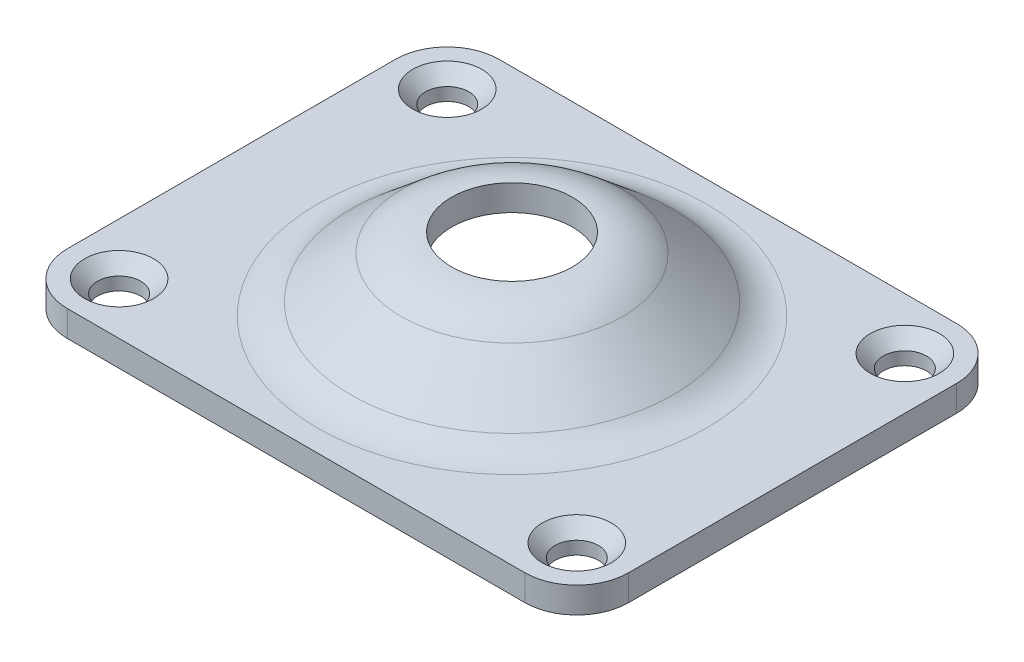
SolidWorks part; units mm, degrees
material "1023 Carbon Steel Sheet (SS)"
ref_plane "Front Plane" through (0, 0, 0) normal (0, 0, 1) x (1, 0, 0)
ref_plane "Top Plane" through (0, 0, 0) normal (0, 1, 0) x (1, 0, 0)
ref_plane "Right Plane" through (0, 0, 0) normal (1, 0, 0) x (0, 0, -1)
sketch "Sketch1" plane through (0, 0, 0) normal (0, 1, 0) x (1, 0, 0)
  line L1 (-26.5, 25) -> (26.5, 25)
  line L2 (-32.5, 19) -> (-32.5, -19)
  line L3 (-26.5, -25) -> (26.5, -25)
  line L4 (32.5, 19) -> (32.5, -19)
  line L5 (-32.5, 25) -> (32.5, -25) construction
  line L6 (-32.5, -25) -> (32.5, 25) construction
  circle A0 centre (-26.5, 19) radius 2.5
  circle A1 centre (26.5, 19) radius 2.5
  circle A2 centre (-26.5, -19) radius 2.5
  circle A3 centre (26.5, -19) radius 2.5
  arc A4 (-32.5, -19) -> (-26.5, -25) centre (-26.5, -19) ccw
  arc A5 (26.5, -25) -> (32.5, -19) centre (26.5, -19) ccw
  arc A6 (26.5, 25) -> (32.5, 19) centre (26.5, 19) cw
  arc A7 (-26.5, 25) -> (-32.5, 19) centre (-26.5, 19) ccw
  circle A8 centre (0, 0) radius 22.5
  point P0 (0, 0)
  dimension "D1" = 6
  dimension "D2" = 5
  dimension "D5" = 45
  dimension "D3" = 65
  dimension "D4" = 50
extrude "Boss-Extrude1" add sketch "Sketch1" along normal blind 3
chamfer "Chamfer1" distance 1.5 angle 45 4 edges at (-26.5, 3, 21.5) (26.5, 3, 21.5) (26.5, 3, -16.5) (-26.5, 3, -16.5)
sketch "Sketch4" plane through (0, 0, 0) normal (0, 0, 1) x (1, 0, 0)
  line L0 (-22.5, 0) -> (-22.5, 3)
  line L1 (26.5, 0) -> (-26.5, 0) construction
  line L2 (-22.5, 0) -> (22.5, 0) construction
  line L3 (22.5, 3) -> (-22.5, 3) construction
  line L4 (-24, 1.5) -> (-22.5, 3) construction
  line L5 (-18.6433, 4.4037) -> (-12.7851, 9.3193)
  line L6 (0, 0) -> (0, 50000) construction
  line L7 (-7, 11.4249) -> (7.8612, 11.4249) construction
  line L8 (-7, 11.4249) -> (-7, 8.4249)
  line L9 (-16.7149, 2.1056) -> (-10.8567, 7.0212)
  arc A0 (-22.5, 3) -> (-18.6433, 4.4037) centre (-22.5, 9) ccw
  arc A1 (-12.7851, 9.3193) -> (-7, 11.4249) centre (-7, 2.4249) cw
  arc A2 (-22.5, 0) -> (-16.7149, 2.1056) centre (-22.5, 9) ccw
  arc A3 (-10.8567, 7.0212) -> (-7, 8.4249) centre (-7, 2.4249) cw
  dimension "D1" = 6
  dimension "D3" = 9
  dimension "D2" = 14
  dimension "D4" = 50
  dimension "D5" = 3
  dimension "D6" = 3
revolve "Revolve1" add sketch "Sketch4" angle 360 about L6
